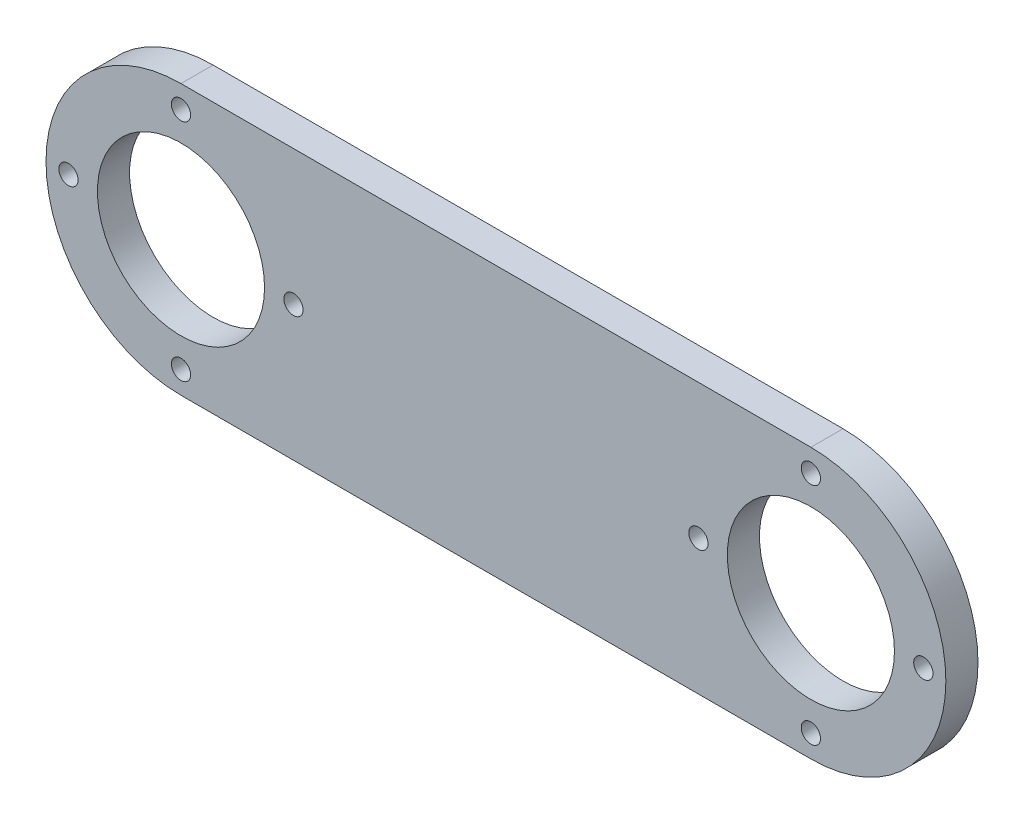
SolidWorks part; units mm, degrees
material "Thornel Mat VMA"
ref_plane "Front Plane" through (0, 0, 0) normal (0, 0, 1) x (1, 0, 0)
ref_plane "Top Plane" through (0, 0, 0) normal (0, 1, 0) x (1, 0, 0)
ref_plane "Right Plane" through (0, 0, 0) normal (1, 0, 0) x (0, 0, -1)
sketch "Sketch1" plane through (0, 0, 0) normal (0, 0, 1) x (1, 0, 0)
  line L0 (49, 26) -> (-49, 26) construction
  line L1 (-49, -16) -> (49, -16) construction
  line L2 (49, 26) -> (-49, 26)
  line L3 (-49, -16) -> (49, -16)
  circle A0 centre (49, 5) radius 21 construction
  circle A1 centre (-49, 5) radius 21 construction
  circle A2 centre (-49, 5) radius 13 construction
  circle A3 centre (-66.5, 5) radius 1.5 construction
  circle A4 centre (-49, 22.5) radius 1.5 construction
  circle A5 centre (-31.5, 5) radius 1.5 construction
  circle A6 centre (-49, -12.5) radius 1.5 construction
  circle A7 centre (49, 5) radius 13 construction
  circle A8 centre (31.5, 5) radius 1.5 construction
  circle A9 centre (49, 22.5) radius 1.5 construction
  circle A10 centre (66.5, 5) radius 1.5 construction
  circle A11 centre (49, -12.5) radius 1.5 construction
  arc A12 (49, -16) -> (49, 26) centre (49, 5) ccw
  arc A13 (-49, 26) -> (-49, -16) centre (-49, 5) ccw
  circle A14 centre (-49, 5) radius 13
  circle A15 centre (-66.5, 5) radius 1.5
  circle A16 centre (-49, 22.5) radius 1.5
  circle A17 centre (-31.5, 5) radius 1.5
  circle A18 centre (-49, -12.5) radius 1.5
  circle A19 centre (49, 5) radius 13
  circle A20 centre (31.5, 5) radius 1.5
  circle A21 centre (49, 22.5) radius 1.5
  circle A22 centre (66.5, 5) radius 1.5
  circle A23 centre (49, -12.5) radius 1.5
extrude "Boss-Extrude1" add sketch "Sketch1" along normal blind 5
